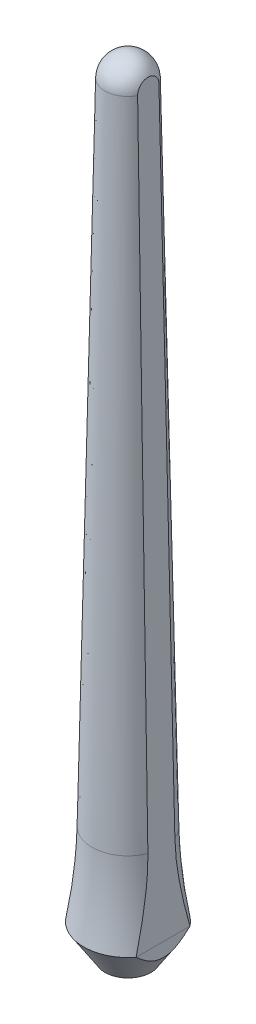
SolidWorks part; units mm, degrees
ref_plane "Front Plane" through (0, 0, 0) normal (0, 0, 1) x (1, 0, 0)
ref_plane "Top Plane" through (0, 0, 0) normal (0, 1, 0) x (1, 0, 0)
ref_plane "Right Plane" through (0, 0, 0) normal (1, 0, 0) x (0, 0, -1)
sketch "Sketch1" plane through (0, 0, 0) normal (0, 0, 1) x (1, 0, 0)
  line L0 (0, 0) -> (0, 120)
  line L1 (3.5, 116.57) -> (5.5, 17.562)
  line L2 (6.75, 5) -> (3.5, 0)
  line L3 (3.5, 0) -> (0, 0)
  line L4 (0, 0) -> (0, -29.0188) construction
  arc A0 (0, 120) -> (3.5, 116.57) centre (0, 116.4993) cw
  arc A1 (5.5, 17.562) -> (6.75, 5) centre (85.4837, 19.1777) ccw
  dimension "D2" = 7
  dimension "D3" = 80
  dimension "D1" = 120
  dimension "D4" = 13.5
  dimension "D5" = 7
  dimension "D6" = 11
  dimension "D7" = 5
revolve "Revolve1" add sketch "Sketch1" angle 360 about L4
sketch "Sketch2" plane through (0, 0, 0) normal (0, -1, 0) x (1, 0, 0)
  circle A0 centre (0, 0) radius 2.2
  dimension "D1" = 4.4
extrude "Cut-Extrude1" cut sketch "Sketch2" against normal blind 12
ref_plane "Plane1" through (0, 5, 0) normal (0, -1, 0) x (-1, 0, 0)
sketch "Sketch3" plane through (0, 0, 0) normal (0, 0, 1) x (1, 0, 0)
  line L0 (2.8286, 130) -> (5.8587, -20)
  line L1 (5.8587, -20) -> (20, -20)
  line L2 (20, -20) -> (20, 130)
  line L3 (20, 130) -> (2.8286, 130)
  line L4 (3.5, 116.57) -> (5.5, 17.562) construction
  line L5 (0, 0) -> (0, -29.0188) construction
  dimension "D1" = 0.4
  dimension "D2" = 150
  dimension "D3" = 20
  dimension "D4" = 20
extrude "Cut-Extrude2" cut sketch "Sketch3" against normal mid plane 20
pattern_circular "CirPattern1" [suppressed] count 3 over 360 about axis through (0, 0, 0) along (0, -1, 0)
chamfer "Chamfer1" distance 0.2 angle 75 1 edges at (0, 0, -2.2)
split "Split1" trim tools "Plane1" bodies to split 105 resulting bodies 109 110
chamfer "Chamfer2" distance 0.5 angle 45 1 edges at (0, 12, -2.2)
